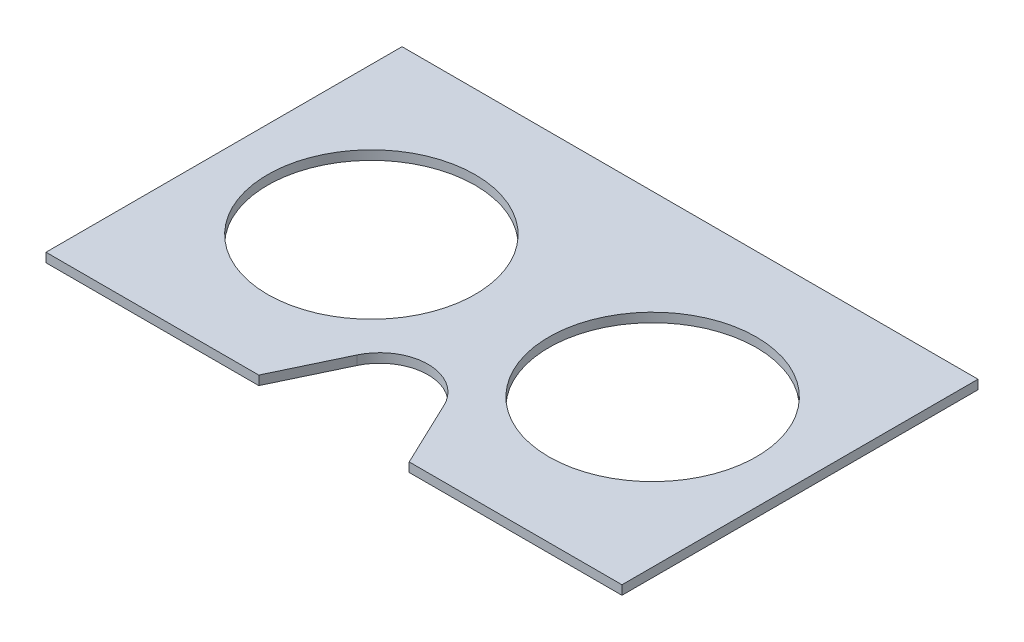
SolidWorks part; units mm, degrees
ref_plane "前视基准面" through (0, 0, 0) normal (0, 0, 1) x (1, 0, 0)
ref_plane "上视基准面" through (0, 0, 0) normal (0, 1, 0) x (1, 0, 0)
ref_plane "右视基准面" through (0, 0, 0) normal (1, 0, 0) x (0, 0, -1)
sketch "草图1" plane through (0, 0, 0) normal (0, 1, 0) x (1, 0, 0)
  line L0 (0, -77.7) -> (46.435, -77.7)
  line L1 (0, 0) -> (125.7, 0)
  line L2 (0, 0) -> (0, -77.7)
  line L3 (0, -77.7) -> (125.7, -77.7) construction
  line L4 (125.7, 0) -> (125.7, -77.7)
  line L5 (125.7, -77.7) -> (79.265, -77.7)
  line L6 (46.435, -77.7) -> (79.265, -77.7) construction
  line L7 (46.435, -77.7) -> (53.35, -63.1783)
  line L8 (79.265, -77.7) -> (72.35, -63.1783)
  line L9 (62.85, -77.7) -> (62.85, -65.9706) construction
  line L10 (52.0056, -57.18) -> (75.401, -57.18) construction
  circle A0 centre (32.16, -38.85) radius 22.65
  circle A1 centre (93.54, -38.85) radius 22.65
  arc A2 (53.35, -63.1783) -> (72.35, -63.1783) centre (62.85, -67.7021) cw
  point P9 (0, -38.85)
  point P10 (62.85, -77.7)
  dimension "D5" = 45.3
  dimension "D6" = 45.3
  dimension "D1" = 125.7
  dimension "D2" = 77.7
  dimension "D3" = 32.16
  dimension "D4" = 32.16
  dimension "D7" = 32.83
  dimension "D8" = 20.52
  dimension "D9" = 19
extrude "凸台-拉伸1" add sketch "草图1" along normal blind 2
